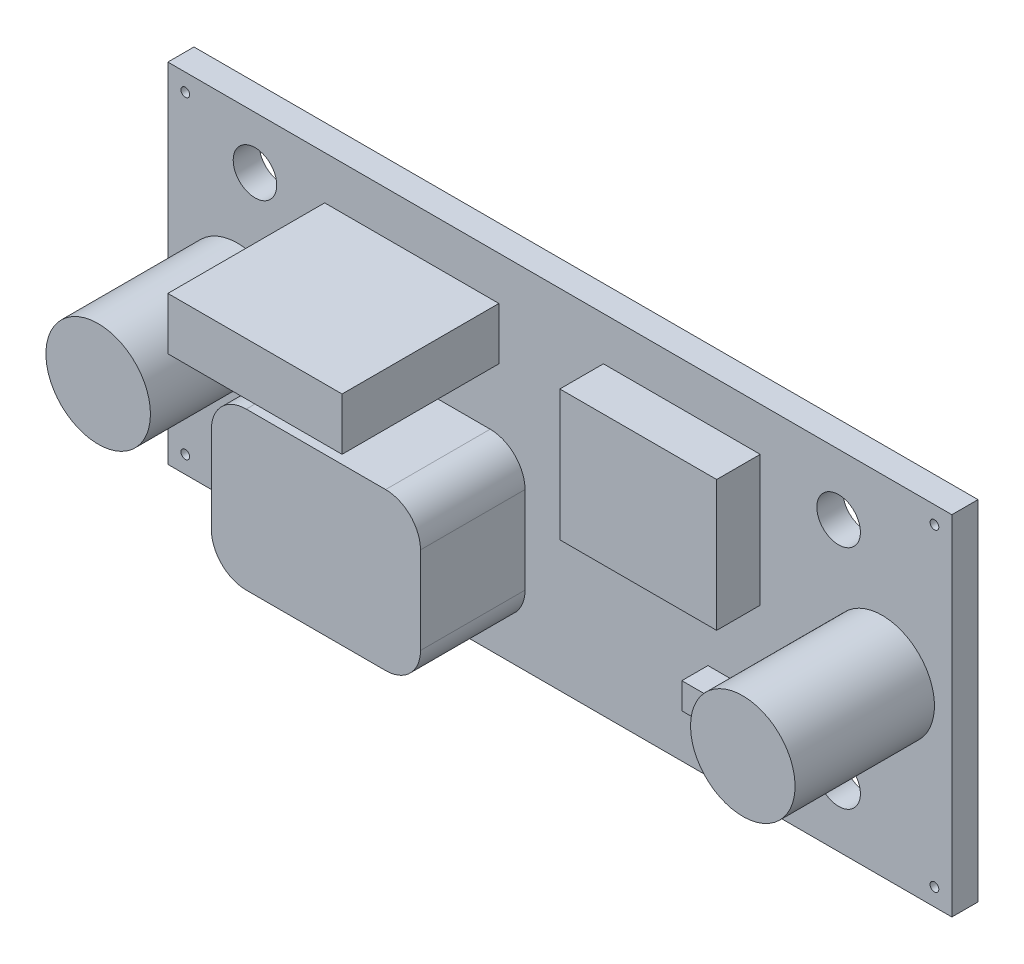
SolidWorks part; units mm, degrees
ref_plane "Front Plane" through (0, 0, 0) normal (0, 0, 1) x (1, 0, 0)
ref_plane "Top Plane" through (0, 0, 0) normal (0, 1, 0) x (1, 0, 0)
ref_plane "Right Plane" through (0, 0, 0) normal (1, 0, 0) x (0, 0, -1)
sketch "Sketch1" plane through (0, 0, 0) normal (0, 0, 1) x (1, 0, 0)
  line L1 (-22.5, 10) -> (22.5, 10)
  line L2 (-22.5, 10) -> (-22.5, -10)
  line L3 (-22.5, -10) -> (22.5, -10)
  line L4 (22.5, 10) -> (22.5, -10)
  line L5 (-22.5, 10) -> (22.5, -10) construction
  line L6 (-22.5, -10) -> (22.5, 10) construction
  point P0 (0, 0)
  dimension "D1" = 45
  dimension "D2" = 20
extrude "Boss-Extrude1" add sketch "Sketch1" along normal blind 1.5
sketch "Sketch2" plane through (0, 0, 1.5) normal (0, 0, 1) x (1, 0, 0)
  line L0 (-22.5, 10) -> (-22.5, -10) construction
  line L1 (-22.5, -10) -> (22.5, -10) construction
  line L2 (0, 9.2301) -> (0, -9.3624) construction
  circle A0 centre (-18.5, 0) radius 3
  circle A1 centre (18.5, 0) radius 3
  dimension "D2" = 6
  dimension "D1" = 4
  dimension "D3" = 10
extrude "Boss-Extrude3" add sketch "Sketch2" along normal blind 8
sketch "Sketch3" plane through (0, 0, 1.5) normal (0, 0, 1) x (1, 0, 0)
  line L0 (0, 9.0316) -> (0, -8.6346) construction
  line L1 (22.5, 10) -> (-22.5, 10) construction
  line L2 (-13.5, 7.5) -> (-3.5, 7.5)
  line L3 (-13.5, 7.5) -> (-13.5, 4.5)
  line L4 (-13.5, 4.5) -> (-3.5, 4.5)
  line L5 (-3.5, 7.5) -> (-3.5, 4.5)
  line L6 (-13.5, 7.5) -> (-3.5, 4.5) construction
  line L7 (-13.5, 4.5) -> (-3.5, 7.5) construction
  line L8 (-22.5, 10) -> (-22.5, -10) construction
  point P2 (-8.5, 6)
  dimension "D1" = 10
  dimension "D2" = 3
  dimension "D3" = 2.5
  dimension "D4" = 9
extrude "Boss-Extrude4" add sketch "Sketch3" along normal blind 9
sketch "Sketch5" plane through (0, 0, 1.5) normal (0, 0, 1) x (1, 0, 0)
  line L0 (-22.5, -10) -> (22.5, -10) construction
  line L1 (-12, 1) -> (-4, 1)
  line L2 (-14, -1) -> (-14, -6)
  line L3 (-12, -8) -> (-4, -8)
  line L4 (-2, -1) -> (-2, -6)
  line L5 (-14, 1) -> (-2, -8) construction
  line L6 (-14, -8) -> (-2, 1) construction
  line L7 (-22.5, 10) -> (-22.5, -10) construction
  arc A0 (-14, -6) -> (-12, -8) centre (-12, -6) ccw
  arc A1 (-4, -8) -> (-2, -6) centre (-4, -6) ccw
  arc A2 (-2, -1) -> (-4, 1) centre (-4, -1) ccw
  arc A3 (-12, 1) -> (-14, -1) centre (-12, -1) ccw
  point P0 (-8, -3.5)
  dimension "D5" = 2
  dimension "D1" = 12
  dimension "D2" = 9
  dimension "D3" = 2
  dimension "D4" = 8.5
extrude "Boss-Extrude5" add sketch "Sketch5" along normal blind 6
sketch "Sketch6" plane through (0, 0, 1.5) normal (0, 0, 1) x (1, 0, 0)
  line L0 (22.5, 10) -> (-22.5, 10) construction
  line L1 (2.5, 7.5) -> (11.5, 7.5)
  line L2 (2.5, 7.5) -> (2.5, 0)
  line L3 (2.5, 0) -> (11.5, 0)
  line L4 (11.5, 7.5) -> (11.5, 0)
  line L5 (2.5, 7.5) -> (11.5, 0) construction
  line L6 (2.5, 0) -> (11.5, 7.5) construction
  line L7 (22.5, -10) -> (22.5, 10) construction
  point P0 (7, 3.75)
  dimension "D1" = 7.5
  dimension "D2" = 2.5
  dimension "D3" = 9
  dimension "D4" = 11
extrude "Boss-Extrude6" add sketch "Sketch6" along normal blind 2.5
sketch "Sketch7" plane through (0, 0, 1.5) normal (0, 0, 1) x (1, 0, 0)
  line L0 (-22.5, -10) -> (22.5, -10) construction
  line L7 (8.5, -4.5) -> (11.5, -4.5)
  line L8 (8.5, -4.5) -> (8.5, -6)
  line L9 (8.5, -6) -> (11.5, -6)
  line L10 (11.5, -4.5) -> (11.5, -6)
  line L11 (8.5, -4.5) -> (11.5, -6) construction
  line L12 (8.5, -6) -> (11.5, -4.5) construction
  line L13 (22.5, -10) -> (22.5, 10) construction
  point P5 (10, -5.25)
  dimension "D1" = 3
  dimension "D2" = 1.5
  dimension "D5" = 4
  dimension "D6" = 11
extrude "Boss-Extrude7" add sketch "Sketch7" along normal blind 1.5
sketch "Sketch9" plane through (0, 0, 1.5) normal (0, 0, 1) x (1, 0, 0)
  line L0 (-22.5, -10) -> (22.5, -10) construction
  line L1 (-22.5, 10) -> (-22.5, -10) construction
  line L2 (-22.5, 0) -> (23.3812, 0) construction
  circle A0 centre (-17.5, -7) radius 1.25
  circle A1 centre (-17.5, 7) radius 1.25
  dimension "D1" = 2.5
  dimension "D2" = 3
  dimension "D3" = 5
extrude "Cut-Extrude1" cut sketch "Sketch9" against normal through all
sketch "Sketch10" plane through (0, 0, 1.5) normal (0, 0, 1) x (1, 0, 0)
  line L0 (22.5, -10) -> (22.5, 10) construction
  line L1 (-22.5, -10) -> (22.5, -10) construction
  line L2 (22.9406, 0) -> (-23.455, 0) construction
  circle A0 centre (16, 6.5) radius 1.25
  circle A1 centre (16, -6.5) radius 1.25
  circle A2 centre (-17.5, -7) radius 1.25 construction
  dimension "D1" = 2.5
  dimension "D2" = 6.5
  dimension "D3" = 16.5
extrude "Cut-Extrude2" cut sketch "Sketch10" against normal through all
sketch "Sketch12" plane through (0, 0, 1.5) normal (0, 0, 1) x (1, 0, 0)
  line L0 (-22.5, 10) -> (-22.5, -10) construction
  line L1 (22.5, 10) -> (-22.5, 10) construction
  line L2 (22.5, -10) -> (22.5, 10) construction
  line L3 (-22.5, -10) -> (22.5, -10) construction
  circle A0 centre (-21.5, 9) radius 0.25
  circle A1 centre (21.5, 9) radius 0.25
  circle A2 centre (21.5, -9) radius 0.25
  circle A3 centre (-21.5, -9) radius 0.25
  point P16 (15.895, -4.9986)
  point P20 (-17.5913, -4.9986)
  dimension "D1" = 0.5
  dimension "D2" = 0.5
  dimension "D3" = 0.5
  dimension "D4" = 0.5
  dimension "D5" = 1
  dimension "D6" = 1
  dimension "D7" = 1
  dimension "D8" = 1
  dimension "D9" = 1
  dimension "D10" = 1
  dimension "D11" = 1
  dimension "D12" = 1
extrude "Cut-Extrude3" cut sketch "Sketch12" against normal blind 1.5
